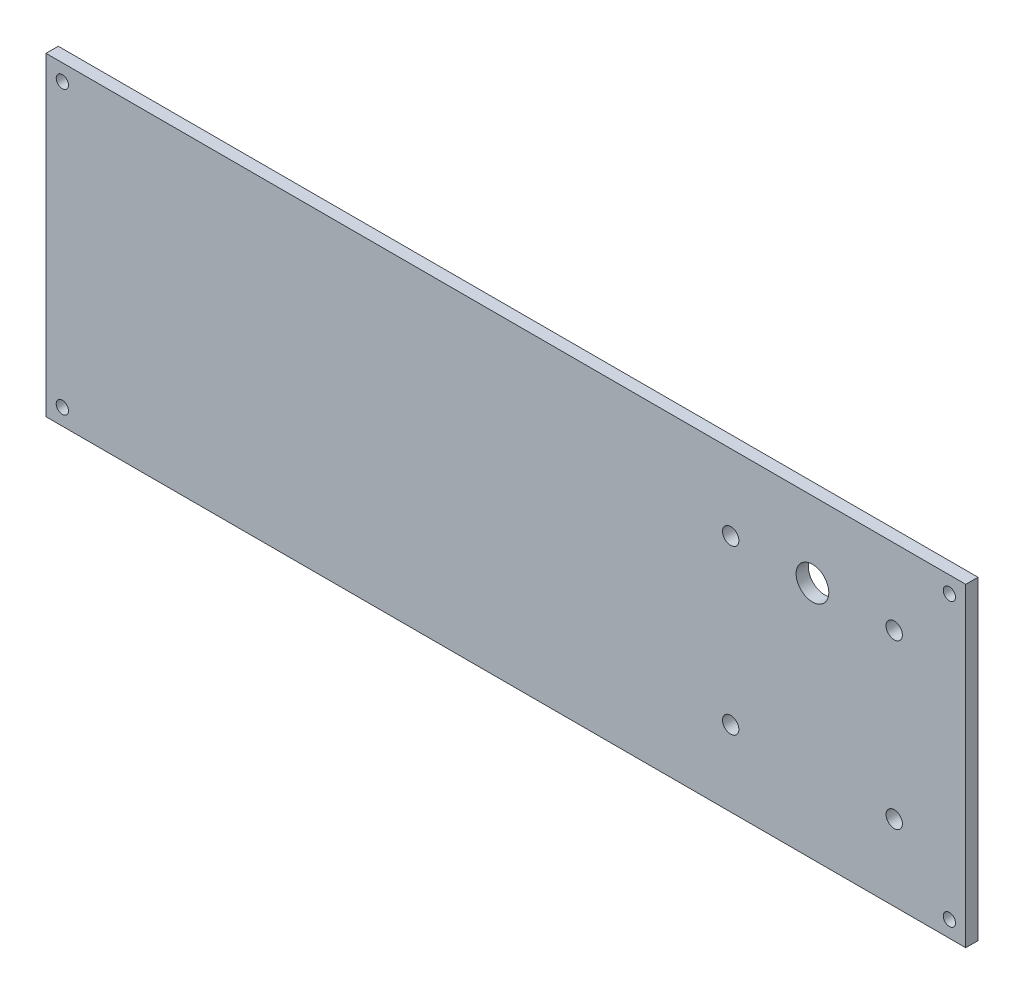
SolidWorks part; units mm, degrees
ref_plane "前视基准面" through (0, 0, 0) normal (0, 0, 1) x (1, 0, 0)
ref_plane "上视基准面" through (0, 0, 0) normal (0, 1, 0) x (1, 0, 0)
ref_plane "右视基准面" through (0, 0, 0) normal (1, 0, 0) x (0, 0, -1)
sketch "草图1" plane through (0, 0, 0) normal (0, 0, 1) x (1, 0, 0)
  line L1 (7.8468, 21.6171) -> (7.8468, -47.3829) construction
  line L3 (-209.1532, -47.3829) -> (-209.1532, 21.6171) construction
  line L5 (11.8468, 25.6171) -> (11.8468, -51.3829)
  line L7 (-213.1532, -51.3829) -> (-213.1532, 25.6171)
  line L8 (-25.6532, 21.6171) -> (-25.6532, -47.3829) construction
  line L9 (-25.6532, -12.8829) -> (-5.6532, -12.8829) construction
  line L10 (-5.6532, -12.8829) -> (-5.6532, -32.8829) construction
  line L11 (-45.6532, 7.1171) -> (-5.6532, 7.1171) construction
  line L12 (-63.1532, 25.6171) -> (11.8468, 25.6171) construction
  line L13 (11.8468, -51.3829) -> (-63.1532, -51.3829) construction
  line L14 (7.8468, -47.3829) -> (-59.1532, -47.3829) construction
  line L15 (-59.1532, 21.6171) -> (7.8468, 21.6171) construction
  line L16 (-59.1532, -47.3829) -> (-59.1532, 21.6171) construction
  line L17 (-63.1532, -51.3829) -> (-63.1532, 25.6171) construction
  line L18 (-213.1532, 25.6171) -> (11.8468, 25.6171)
  line L19 (-213.1532, -51.3829) -> (11.8468, -51.3829)
  circle A0 centre (-209.1532, 21.6171) radius 1.5
  circle A1 centre (7.8468, 21.6171) radius 1.5
  circle A2 centre (-209.1532, -47.3829) radius 1.5
  circle A3 centre (7.8468, -47.3829) radius 1.5
  circle A4 centre (-5.6532, -32.8829) radius 2
  circle A8 centre (-45.6532, -32.8829) radius 2
  circle A9 centre (-45.6532, 7.1171) radius 2
  circle A10 centre (-5.6532, 7.1171) radius 2
  circle A11 centre (-25.6532, 7.1171) radius 4
  dimension "D3" = 4
extrude "凸台-拉伸1" add sketch "草图1" along normal blind 3
